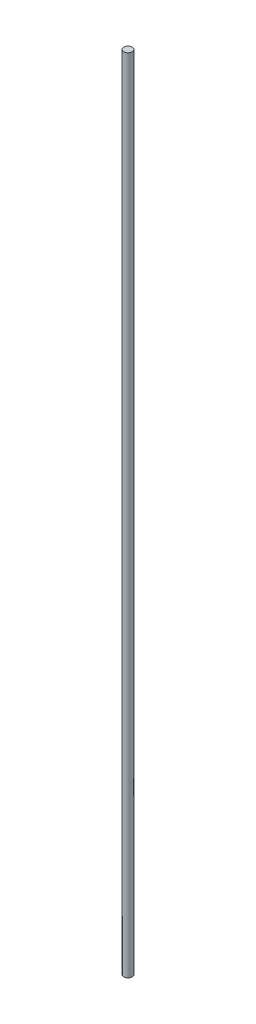
SolidWorks part; units mm, degrees
ref_plane "Front Plane" through (0, 0, 0) normal (0, 0, 1) x (1, 0, 0)
ref_plane "Top Plane" through (0, 0, 0) normal (0, 1, 0) x (1, 0, 0)
ref_plane "Right Plane" through (0, 0, 0) normal (1, 0, 0) x (0, 0, -1)
sketch "Sketch1" plane through (0, 0, 0) normal (0, 1, 0) x (1, 0, 0)
  circle A0 centre (0, 0) radius 3.175
  dimension "D1" = 6.35
extrude "Boss-Extrude1" add sketch "Sketch1" along normal mid plane 609.6
